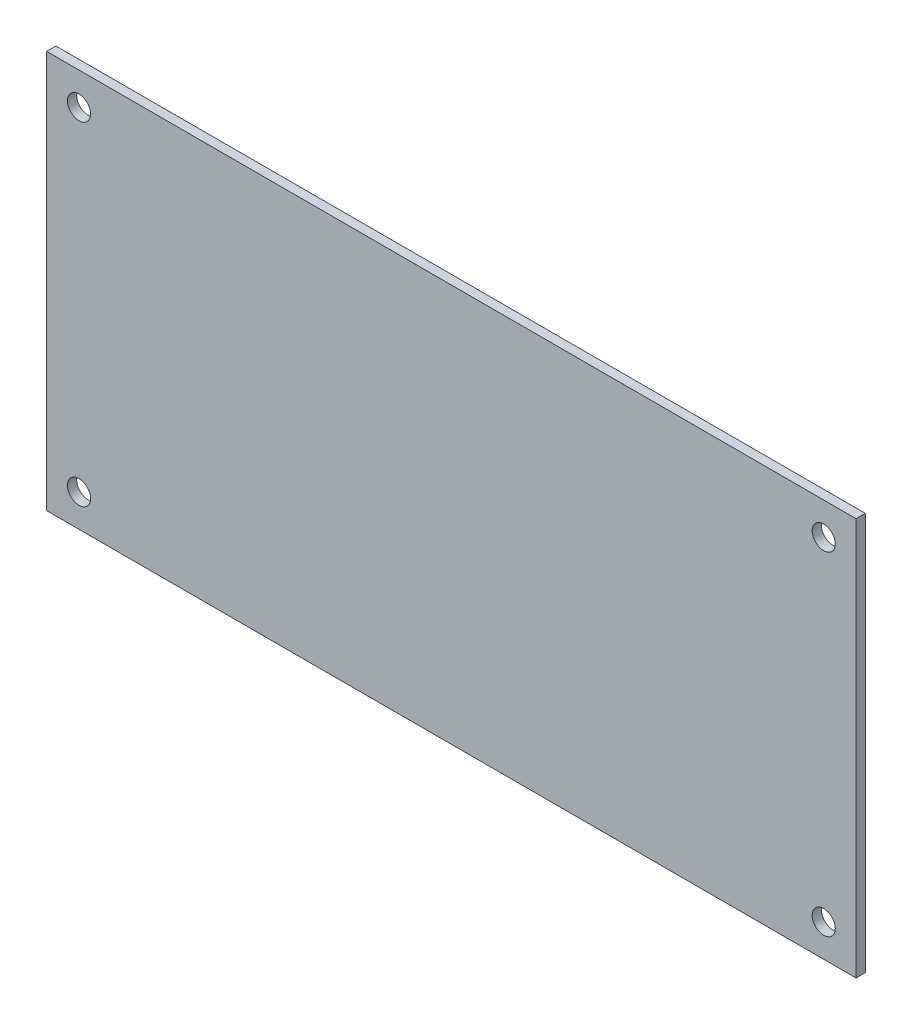
SolidWorks part; units mm, degrees
ref_plane "Ön Düzlem" through (0, 0, 0) normal (0, 0, 1) x (1, 0, 0)
ref_plane "Üst Düzlem" through (0, 0, 0) normal (0, 1, 0) x (1, 0, 0)
ref_plane "Sağ Düzlem" through (0, 0, 0) normal (1, 0, 0) x (0, 0, -1)
sketch "Çizim1" plane through (0, 0, 0) normal (0, 0, 1) x (1, 0, 0)
  line L1 (0, 0) -> (175, 0)
  line L2 (0, 0) -> (0, 86)
  line L3 (0, 86) -> (175, 86)
  line L4 (175, 0) -> (175, 86)
  line L5 (7, 79) -> (168, 79) construction
  line L6 (7, 79) -> (7, 7) construction
  line L7 (7, 7) -> (168, 7) construction
  line L8 (168, 79) -> (168, 7) construction
  circle A0 centre (7, 79) radius 2.5
  circle A1 centre (168, 79) radius 2.5
  circle A2 centre (7, 7) radius 2.5
  circle A3 centre (168, 7) radius 2.5
  dimension "D1" = 175
  dimension "D2" = 86
  dimension "D3" = 72
  dimension "D4" = 161
  dimension "D5" = 7
  dimension "D6" = 7
extrude "Yükseklik-Ekstrüzyon1" add sketch "Çizim1" along normal blind 2
